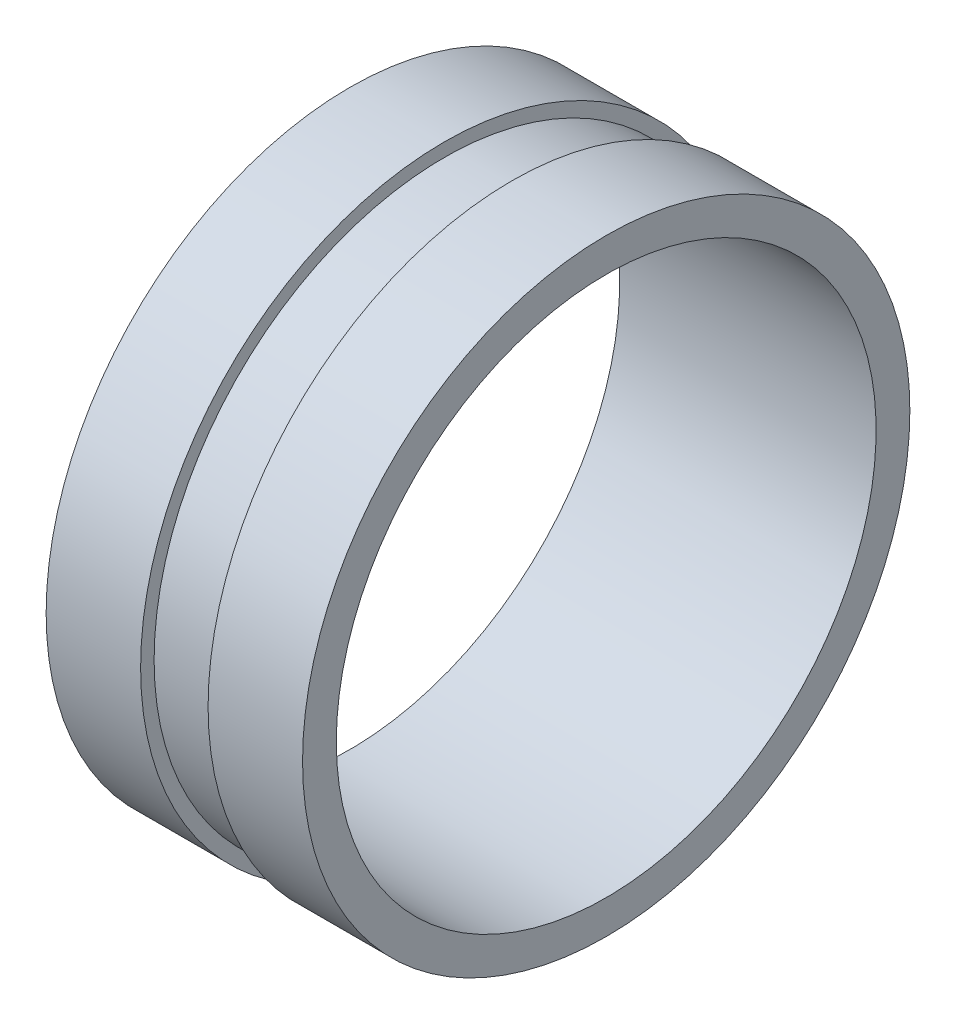
SolidWorks part; units mm, degrees
ref_plane "Front Plane" through (0, 0, 0) normal (0, 0, 1) x (1, 0, 0)
ref_plane "Top Plane" through (0, 0, 0) normal (0, 1, 0) x (1, 0, 0)
ref_plane "Right Plane" through (0, 0, 0) normal (1, 0, 0) x (0, 0, -1)
sketch "Sketch1" plane through (0, 0, 0) normal (1, 0, 0) x (0, 0, -1)
  circle A0 centre (0, 0) radius 25.4
  circle A1 centre (0, 0) radius 28.575
  dimension "D1" = 50.8
  dimension "D2" = 57.15
extrude "Boss-Extrude1" add sketch "Sketch1" along normal blind 24.13
sketch "Sketch2" plane through (0, 0, 0) normal (0, 0, 1) x (1, 0, 0)
  line L1 (24.13, 28.575) -> (0, 28.575) construction
  line L2 (15.24, 28.575) -> (15.24, 27.305)
  line L3 (15.24, 27.305) -> (8.89, 27.305)
  line L4 (8.89, 27.305) -> (8.89, 28.575)
  line L6 (15.24, 28.575) -> (15.24, 30.6286)
  line L7 (15.24, 30.6286) -> (8.89, 30.6286)
  line L8 (8.89, 30.6286) -> (8.89, 28.575)
  dimension "D1" = 1.27
sweep "Cut-Sweep1" cut profiles "Sketch2" path edge at (24.13, 0, -28.575)
sketch "Sketch3" plane through (0, 0, 0) normal (0, 1, 0) x (1, 0, 0)
  line L1 (8.89, -27.305) -> (15.24, -27.305) construction
  line L2 (8.89, -27.305) -> (15.24, -27.305) construction
